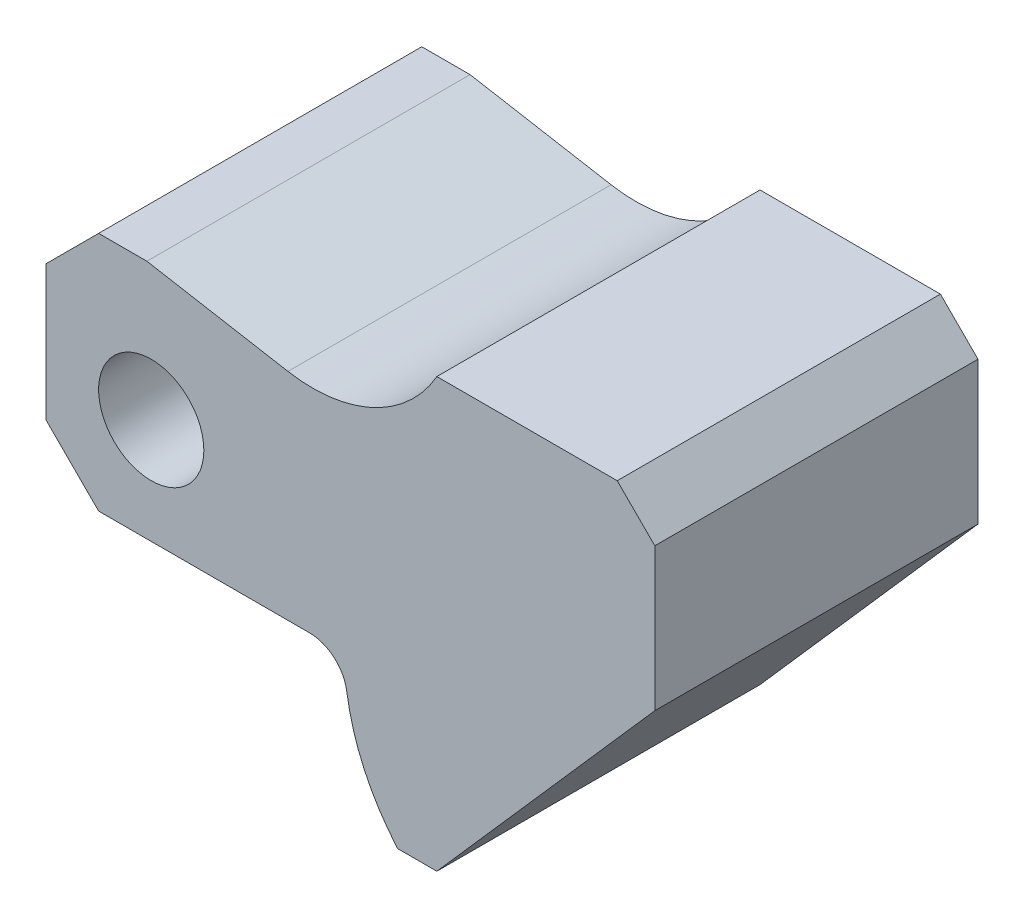
SolidWorks part; units mm, degrees
material "AISI 1020"
ref_plane "Front Plane" through (0, 0, 0) normal (0, 0, 1) x (1, 0, 0)
ref_plane "Top Plane" through (0, 0, 0) normal (0, 1, 0) x (1, 0, 0)
ref_plane "Right Plane" through (0, 0, 0) normal (1, 0, 0) x (0, 0, -1)
sketch "Sketch1" plane through (0, 0, 0) normal (0, 0, 1) x (1, 0, 0)
  line L0 (0, 0) -> (-7, 7)
  line L1 (-7, 7) -> (-7, 25)
  line L2 (-7, 25) -> (0, 32)
  line L3 (0, 32) -> (6.4231, 32)
  line L4 (45, 38) -> (69, 38)
  line L5 (69, 38) -> (74, 33)
  line L6 (74, 33) -> (74, 14)
  line L7 (74, 14) -> (45, -19)
  line L8 (45, -19) -> (39.7881, -19)
  line L10 (28.0666, 0) -> (0, 0)
  line L11 (-7, 14) -> (7, 14) construction
  line L12 (61.697, -19) -> (61.697, 0) construction
  line L13 (6.4231, 32) -> (16.9623, 32) construction
  line L14 (6.4231, 32) -> (25.1901, 28.6909)
  circle A0 centre (7, 14) radius 7
  arc A1 (33.0123, -4.2647) -> (28.0666, 0) centre (28.0666, -5) ccw
  arc A2 (39.7881, -19) -> (33.0123, -4.2647) centre (61.697, 0) cw
  arc A3 (45, 38) -> (25.1901, 28.6909) centre (28.4894, 47.4022) cw
  point P18 (0, 0)
  point P23 (22.0705, 29.2409)
  point P25 (0, 0)
  point P26 (61.697, 0)
  dimension "D5" = 45
  dimension "D17" = 5
  dimension "D20" = 10
  dimension "D21" = 19
  dimension "D1" = 7
  dimension "D2" = 32
  dimension "D3" = 14
  dimension "D4" = 14
  dimension "D6" = 19
  dimension "D7" = 14
  dimension "D8" = 7
  dimension "D9" = 45
  dimension "D10" = 14
  dimension "D11" = 29
  dimension "D12" = 45
  dimension "D13" = 5
  dimension "D14" = 24
  dimension "D15" = 81
  dimension "D16" = 57
  dimension "D18" = 19
  dimension "D19" = 29
extrude "Boss-Extrude1" add sketch "Sketch1" along normal blind 43
